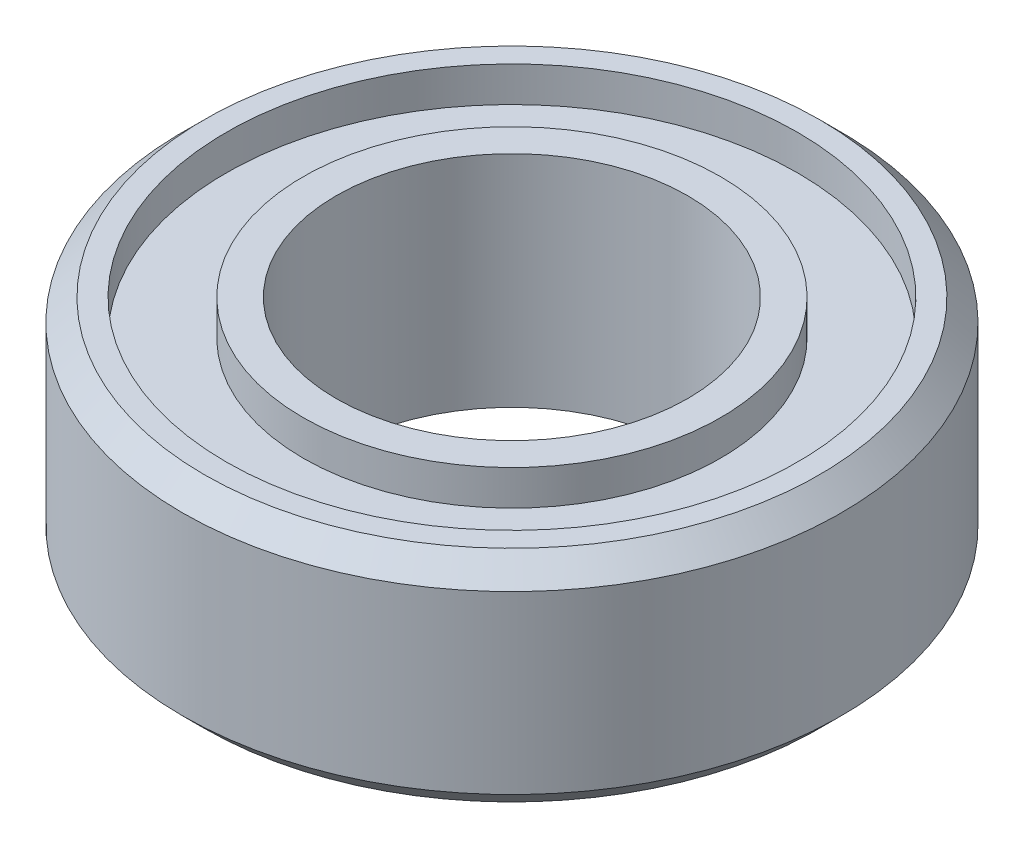
SolidWorks part; units mm, degrees
ref_plane "前视基准面" through (0, 0, 0) normal (0, 0, 1) x (1, 0, 0)
ref_plane "上视基准面" through (0, 0, 0) normal (0, 1, 0) x (1, 0, 0)
ref_plane "右视基准面" through (0, 0, 0) normal (1, 0, 0) x (0, 0, -1)
sketch "草图1" plane through (0, 0, 0) normal (0, 1, 0) x (1, 0, 0)
  circle A0 centre (0, 0) radius 7.5
  circle A1 centre (0, 0) radius 4
  dimension "D1" = 15
  dimension "D2" = 8
extrude "凸台-拉伸1" add sketch "草图1" along normal blind 5
chamfer "倒角1" distance 0.5 angle 45 1 edges at (0, 5, 7.5)
chamfer "倒角2" distance 0.5 angle 45 1 edges at (0, 0, 7.5)
sketch "草图2" plane through (0, 5, 0) normal (0, 1, 0) x (1, 0, 0)
  circle A0 centre (0, 0) radius 4.75
  circle A1 centre (0, 0) radius 6.5
  dimension "D1" = 9.5
  dimension "D2" = 13
extrude "切除-拉伸1" cut sketch "草图2" against normal blind 0.8
sketch "草图3" plane through (0, 0, 0) normal (0, -1, 0) x (1, 0, 0)
  circle A1 centre (0, 0) radius 6.5
  circle A2 centre (0, 0) radius 6.5
  circle A3 centre (0, 0) radius 4.75
  circle A4 centre (0, 0) radius 4.75
  dimension "D1" = 0
  dimension "D2" = 0
extrude "切除-拉伸2" cut sketch "草图3" against normal blind 0.8
